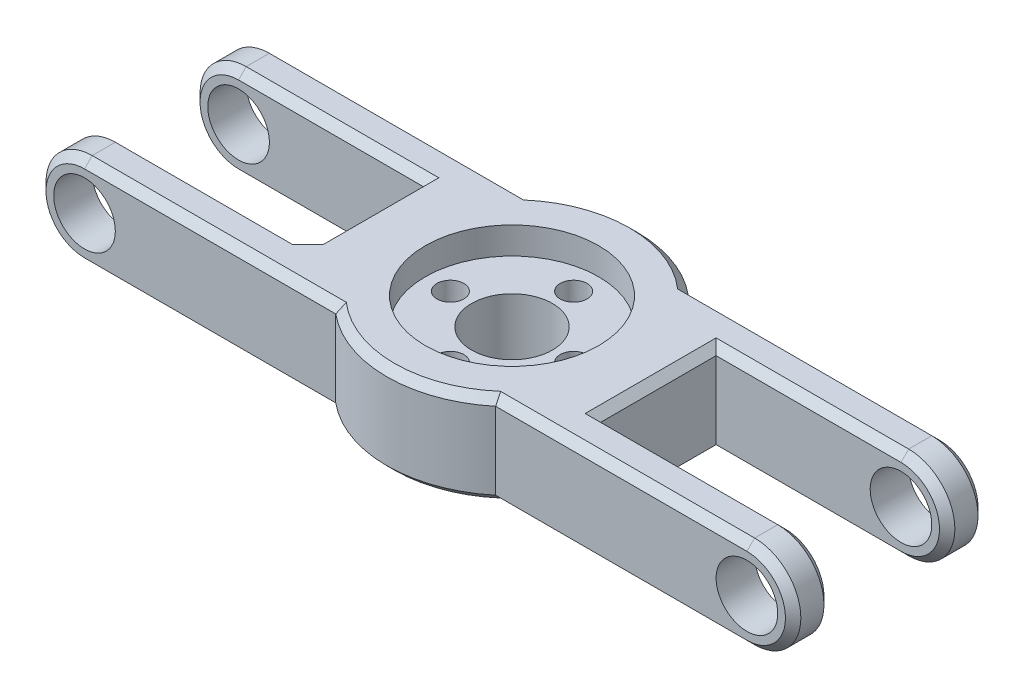
SolidWorks part; units mm, degrees
ref_plane "Alzado" through (0, 0, 0) normal (0, 0, 1) x (1, 0, 0)
ref_plane "Planta" through (0, 0, 0) normal (0, 1, 0) x (1, 0, 0)
ref_plane "Vista lateral" through (0, 0, 0) normal (1, 0, 0) x (0, 0, -1)
sketch "Croquis1" plane through (0, 0, 0) normal (0, 0, 1) x (1, 0, 0)
  line L0 (-43, 0) -> (43, 0) construction
  line L1 (-43, 6) -> (43, 6)
  line L2 (-43, -6) -> (43, -6)
  arc A0 (-43, 6) -> (-43, -6) centre (-43, 0) ccw
  arc A1 (43, -6) -> (43, 6) centre (43, 0) ccw
  circle A2 centre (-43, 0) radius 4
  circle A3 centre (43, 0) radius 4
  point P2 (0, 0)
  dimension "D3" = 8
  dimension "D1" = 12
  dimension "D2" = 86
extrude "Saliente-Extruir1" add sketch "Croquis1" along normal mid plane 25
sketch "Croquis2" plane through (0, 6, 0) normal (0, 1, 0) x (1, 0, 0)
  line L0 (-49, 12.5) -> (-49, -12.5) construction
  line L1 (-49, 7.5) -> (-19, 7.5)
  line L2 (-49, 7.5) -> (-49, -7.5)
  line L3 (-49, -7.5) -> (-19, -7.5)
  line L4 (-19, 7.5) -> (-19, -7.5)
  line L5 (0, -6.6) -> (0, 6.6) construction
  line L6 (19, 7.5) -> (19, -7.5)
  line L7 (49, -7.5) -> (19, -7.5)
  line L8 (49, 7.5) -> (49, -7.5)
  line L9 (49, 7.5) -> (19, 7.5)
  point P6 (-19, 0)
  dimension "D1" = 30
  dimension "D2" = 15
extrude "Cortar-Extruir1" cut sketch "Croquis2" against normal through all
sketch "Croquis3" plane through (0, 6, 0) normal (0, 1, 0) x (1, 0, 0)
  circle A0 centre (0, 0) radius 4
  dimension "D1" = 8
extrude "Cortar-Extruir2" cut sketch "Croquis3" against normal through all
sketch "Croquis4" plane through (0, 6, 0) normal (0, 1, 0) x (1, 0, 0)
  circle A0 centre (0, 0) radius 11.25
  dimension "D1" = 22.5
extrude "Cortar-Extruir3" cut sketch "Croquis4" against normal blind 3.5
sketch "Croquis5" plane through (0, 2.5, 0) normal (0, 1, 0) x (1, 0, 0)
  circle A0 centre (0, 0) radius 5.25
  dimension "D1" = 10.5
extrude "Cortar-Extruir4" cut sketch "Croquis5" against normal through all both and the other way through all
sketch "Croquis6" plane through (0, 6, 0) normal (0, 1, 0) x (1, 0, 0)
  circle A1 centre (0, 0) radius 11.25 construction
  circle A2 centre (0, 0) radius 16.25
  circle A3 centre (0, 0) radius 16.25
  circle A4 centre (0, 0) radius 11.25
  dimension "D1" = 5
extrude "Saliente-Extruir2" add sketch "Croquis6" against normal up to surface (12 mm away) up to face at (0, -6, 5.25)
chamfer "Chaflán1" distance 1 angle 45 33 edges at (26.6916, -6, 12.5) (26.6916, 6, 12.5) (49, 0, 12.5) (31, -6, 7.5) (19, -6, 0) (31, -6, -7.5) (49, 0, 7.5) (49, 0, -7.5) (31, 6, 7.5) (19, 6, 0) (31, 6, -7.5) (26.6916, -6, -12.5) (49, 0, -12.5) (26.6916, 6, -12.5) (-26.6916, -6, -12.5) (-49, 0, -12.5) (-26.6916, 6, -12.5) (-31, -6, -7.5) (-31, -6, 7.5) (-49, 0, -7.5) (-49, 0, 7.5) (-19, -6, 0) (-19, 0, 7.5) (-31, 6, -7.5) (-19, 6, 0) (-31, 6, 7.5) (-26.6916, -6, 12.5) (-49, 0, 12.5) (-26.6916, 6, 12.5) (0, -6, -16.25) (0, -6, 16.25) (0, 6, -16.25) (0, 6, 16.25)
sketch "Sketch1" plane through (0, 2.5, 0) normal (0, 1, 0) x (1, 0, 0)
  circle A0 centre (0, 0) radius 8 construction
  circle A1 centre (0, 8) radius 1.75
  dimension "D1" = 16
  dimension "D2" = 3.5
extrude "Cut-Extrude1" cut sketch "Sketch1" against normal blind 10
pattern_circular "CirPattern1" count 4 over 360 about axis through (0, 0, 0) along (0, 1, 0) of "Cut-Extrude1"
